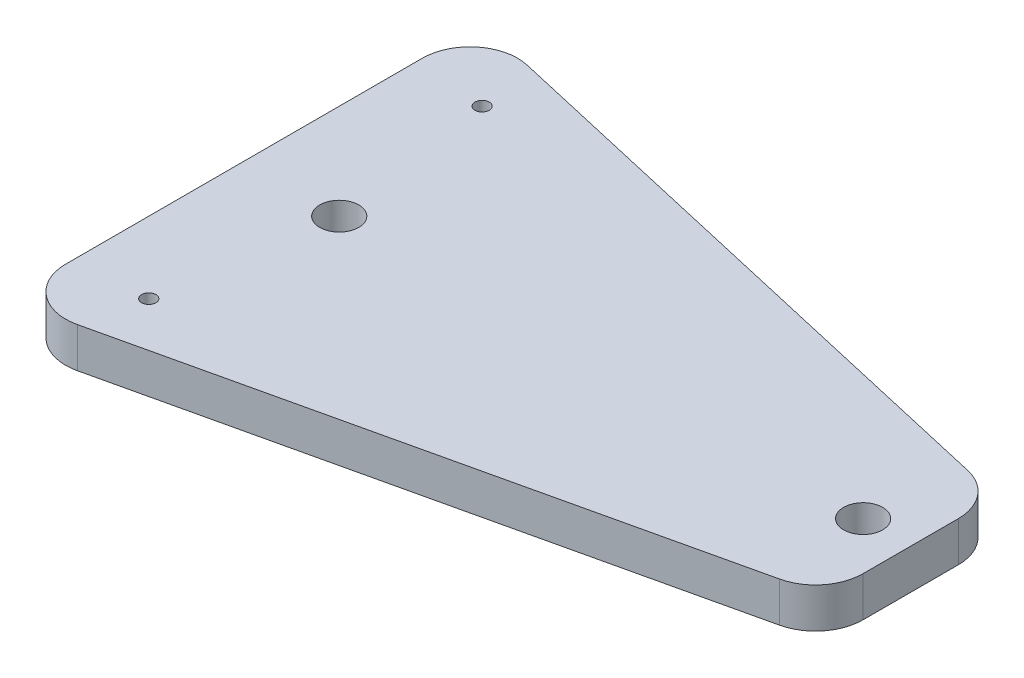
SolidWorks part; units mm, degrees
ref_plane "正面" through (0, 0, 0) normal (0, 0, 1) x (1, 0, 0)
ref_plane "平面" through (0, 0, 0) normal (0, 1, 0) x (1, 0, 0)
ref_plane "右側面" through (0, 0, 0) normal (1, 0, 0) x (0, 0, -1)
sketch "ｽｹｯﾁ1" plane through (0, 0, 0) normal (0, 1, 0) x (1, 0, 0)
  line L0 (-102.9858, 0) -> (37.0142, 0) construction
  line L1 (-90.7556, -47.202) -> (29.2444, -19.7481)
  line L2 (-102.9858, -37.4538) -> (-102.9858, 37.4538)
  line L3 (-90.7556, 47.202) -> (29.2444, 19.7481)
  line L4 (37.0142, -10) -> (37.0142, 10)
  line L5 (-102.9858, -50) -> (37.0142, 17.9705) construction
  line L6 (-102.9858, 50) -> (37.0142, -17.9705) construction
  circle A0 centre (-82.9858, 0) radius 4.1
  circle A1 centre (27.0142, 0) radius 4.1
  arc A2 (29.2444, 19.7481) -> (37.0142, 10) centre (27.0142, 10) cw
  arc A3 (29.2444, -19.7481) -> (37.0142, -10) centre (27.0142, -10) ccw
  arc A4 (-90.7556, -47.202) -> (-102.9858, -37.4538) centre (-92.9858, -37.4538) cw
  arc A5 (-102.9858, 37.4538) -> (-90.7556, 47.202) centre (-92.9858, 37.4538) cw
  circle A6 centre (-87.9858, 35) radius 1.5
  circle A7 centre (-87.9858, -35) radius 1.5
  point P0 (0, 0)
  dimension "D3" = 8.2
  dimension "D6" = 10
  dimension "D7" = 3
  dimension "D2" = 100
  dimension "D4" = 20
  dimension "D5" = 10
  dimension "D8" = 15
  dimension "D9" = 15
  dimension "D10" = 15
  dimension "D11" = 20
  dimension "D12" = 140
extrude "ﾎﾞｽ - 押し出し1" add sketch "ｽｹｯﾁ1" along normal blind 8.4
sketch "ｽｹｯﾁ2" plane through (0, 0, 0) normal (0, -1, 0) x (1, 0, 0)
  line L1 (-93.0858, 29.9) -> (-82.8858, 29.9)
  line L2 (-93.0858, 29.9) -> (-93.0858, 40.1)
  line L3 (-93.0858, 40.1) -> (-82.8858, 40.1)
  line L4 (-82.8858, 29.9) -> (-82.8858, 40.1)
  line L5 (-93.0858, 29.9) -> (-82.8858, 40.1) construction
  line L6 (-93.0858, 40.1) -> (-82.8858, 29.9) construction
  line L7 (-93.0858, -40.1) -> (-82.8858, -40.1)
  line L8 (-93.0858, -40.1) -> (-93.0858, -29.9)
  line L9 (-93.0858, -29.9) -> (-82.8858, -29.9)
  line L10 (-82.8858, -40.1) -> (-82.8858, -29.9)
  line L11 (-93.0858, -40.1) -> (-82.8858, -29.9) construction
  line L12 (-93.0858, -29.9) -> (-82.8858, -40.1) construction
  point P0 (-87.9858, 35)
  point P6 (-87.9858, -35)
  dimension "D1" = 10.2
extrude "ｶｯﾄ - 押し出し1" cut sketch "ｽｹｯﾁ2" against normal blind 5
